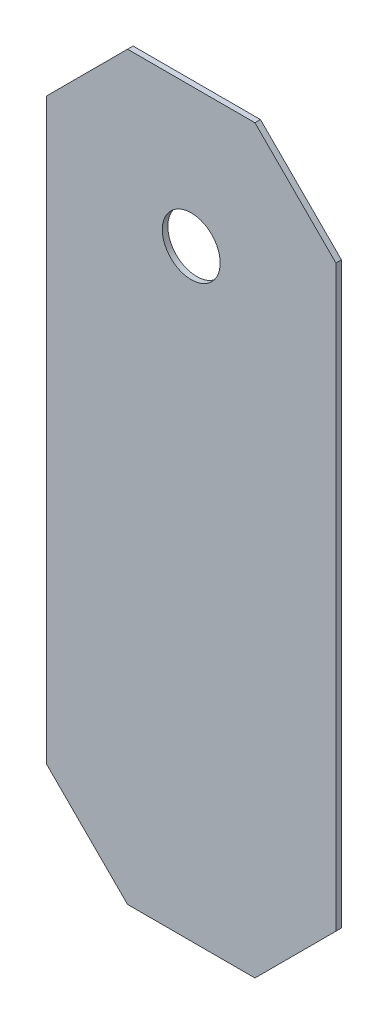
SolidWorks part; units mm, degrees
ref_plane "Спереди" through (0, 0, 0) normal (0, 0, 1) x (1, 0, 0)
ref_plane "Сверху" through (0, 0, 0) normal (0, 1, 0) x (1, 0, 0)
ref_plane "Справа" through (0, 0, 0) normal (1, 0, 0) x (0, 0, -1)
sketch "Эскиз1" plane through (0, 0, 0) normal (0, 0, 1) x (1, 0, 0)
  line L0 (-105, 539.9964) -> (-105, 203.9939)
  line L1 (105, 539.9964) -> (105, 203.9939)
  line L2 (0, 639.9964) -> (0, 656.3633) construction
  line L3 (46.2224, 640.7741) -> (-46.2224, 640.7741)
  line L4 (-105, 539.9964) -> (-105, 581.9964)
  line L5 (-105, 581.9964) -> (-46.2224, 640.7741)
  line L6 (105, 539.9964) -> (105, 581.9964)
  line L7 (105, 581.9964) -> (46.2224, 640.7741)
  line L8 (-100, 371.9952) -> (-247.0361, 371.9952) construction
  line L9 (105, 203.9939) -> (105, 161.9939)
  line L10 (105, 161.9939) -> (46.2224, 103.2162)
  line L11 (46.2224, 103.2162) -> (-46.2224, 103.2162)
  line L12 (-105, 161.9939) -> (-46.2224, 103.2162)
  line L13 (-105, 203.9939) -> (-105, 161.9939)
  circle A3 centre (0, 539.9964) radius 21
extrude "Вытянуть1" add sketch "Эскиз1" along normal blind 4
